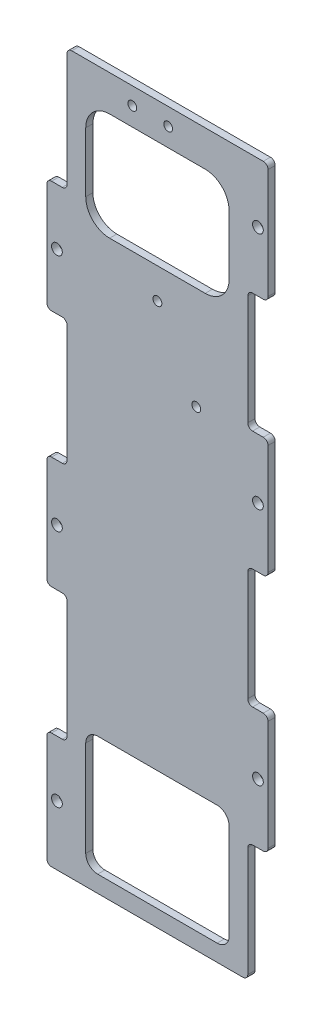
SolidWorks part; units mm, degrees
material "Acrylic (Medium-high impact)"
ref_plane "Front Plane" through (0, 0, 0) normal (0, 0, 1) x (1, 0, 0)
ref_plane "Top Plane" through (0, 0, 0) normal (0, 1, 0) x (1, 0, 0)
ref_plane "Right Plane" through (0, 0, 0) normal (1, 0, 0) x (0, 0, -1)
sketch "Sketch1" plane through (0, 0, 0) normal (0, 0, 1) x (1, 0, 0)
  line L1 (46.3, -150) -> (-46.3, -150)
  line L2 (46.3, -150) -> (46.3, 150)
  line L3 (46.3, 150) -> (-46.3, 150)
  line L4 (-46.3, -150) -> (-46.3, 150)
  line L5 (46.3, -150) -> (-46.3, 150) construction
  line L6 (46.3, 150) -> (-46.3, -150) construction
  point P0 (0, 0)
  dimension "D1" = 92.6
  dimension "D2" = 300
extrude "Boss-Extrude1" add sketch "Sketch1" along normal blind 3
sketch "Sketch2" plane through (0, 0, 0) normal (0, 0, 1) x (1, 0, 0)
  line L0 (-42.06, 150.5) -> (-42.06, -149.5) construction
  line L1 (42.06, 150.5) -> (42.06, -149.5) construction
  line L82 (-37.82, 98.5) -> (-46.3, 98.5)
  line L91 (-37.82, 98.5) -> (-37.82, 150)
  line L104 (-37.82, 150) -> (-46.3, 150)
  line L109 (-46.3, 98.5) -> (-46.3, 150)
  line L112 (-46.3, -150) -> (46.3, -150) construction
  line L115 (-37.82, 98.5) -> (-46.3, 150) construction
  line L116 (-37.82, 150) -> (-46.3, 98.5) construction
  line L121 (37.82, 100) -> (46.3, 100)
  line L122 (37.82, 100) -> (37.82, 50)
  line L127 (37.82, 50) -> (46.3, 50)
  line L128 (46.3, 100) -> (46.3, 50)
  line L133 (37.82, 100) -> (46.3, 50) construction
  line L134 (37.82, 50) -> (46.3, 100) construction
  line L135 (46.3, -50) -> (37.82, -50)
  line L136 (46.3, -50) -> (46.3, 0)
  line L137 (46.3, 0) -> (37.82, 0)
  line L138 (37.82, -50) -> (37.82, 0)
  line L139 (46.3, -50) -> (37.82, 0) construction
  line L140 (46.3, 0) -> (37.82, -50) construction
  line L141 (-37.82, -1.5) -> (-46.3, -1.5)
  line L142 (-37.82, -1.5) -> (-37.82, 51.5)
  line L143 (-37.82, 51.5) -> (-46.3, 51.5)
  line L144 (-46.3, -1.5) -> (-46.3, 51.5)
  line L145 (-37.82, -1.5) -> (-46.3, 51.5) construction
  line L146 (-37.82, 51.5) -> (-46.3, -1.5) construction
  line L147 (-37.82, -101.5) -> (-46.3, -101.5)
  line L148 (-37.82, -101.5) -> (-37.82, -48.5)
  line L149 (-37.82, -48.5) -> (-46.3, -48.5)
  line L150 (-46.3, -101.5) -> (-46.3, -48.5)
  line L151 (-37.82, -101.5) -> (-46.3, -48.5) construction
  line L152 (-37.82, -48.5) -> (-46.3, -101.5) construction
  line L153 (37.82, -150) -> (46.3, -150)
  line L154 (37.82, -150) -> (37.82, -100)
  line L155 (37.82, -100) -> (46.3, -100)
  line L156 (46.3, -150) -> (46.3, -100)
  line L157 (37.82, -150) -> (46.3, -100) construction
  line L158 (37.82, -100) -> (46.3, -150) construction
  line L159 (42.06, 50) -> (-134.3061, 50) construction
  line L160 (46.3, 150) -> (-46.3, 150) construction
  circle A30 centre (-42.06, 75) radius 2.25
  circle A31 centre (42.06, 125) radius 2.25
  circle A32 centre (42.06, 25) radius 2.25
  circle A33 centre (42.06, -75) radius 2.25
  circle A34 centre (-42.06, -25) radius 2.25
  circle A35 centre (-42.06, -125) radius 2.25
  point P8 (-42.06, 124.25)
  point P10 (-42.06, 25)
  point P19 (42.06, 75)
  point P24 (-42.06, -75)
  point P32 (42.06, -25)
  point P39 (42.06, -125)
  dimension "D4" = 84.12
  dimension "D5" = 8.48
  dimension "D15" = 75
  dimension "D17" = 53
  dimension "D23" = 8.48
  dimension "D26" = 0
  dimension "D1" = 4.5
  dimension "D2" = 4.5
  dimension "D12" = 4.5
  dimension "D14" = 4.5
  dimension "D20" = 4.5
  dimension "D22" = 4.5
  dimension "D3" = 25
  dimension "D6" = 51.5
  dimension "D7" = 8.48
  dimension "D8" = 50
  dimension "D9" = 50
  dimension "D10" = 8.48
  dimension "D11" = 75
  dimension "D13" = 100
  dimension "D16" = 53
  dimension "D18" = 8.48
  dimension "D19" = 125
  dimension "D21" = 50
  dimension "D24" = 100
  dimension "D25" = 42.06
  dimension "D27" = 75
  dimension "D28" = 75
  dimension "D29" = 25
  dimension "D30" = 0
  dimension "D31" = 125
extrude "Cut-Extrude1" cut sketch "Sketch2" along normal blind 10
fillet "Fillet1" radius 2 24 edges at (-46.3, 51.5, 1.5) (-37.82, 51.5, 1.5) (-37.82, -1.5, 1.5) (-46.3, -1.5, 1.5) (-46.3, -48.5, 1.5) (-37.82, -48.5, 1.5) (-37.82, -101.5, 1.5) (-46.3, -101.5, 1.5) (-46.3, -150, 1.5) (37.82, -150, 1.5) (37.82, -100, 1.5) (46.3, -100, 1.5) (46.3, -50, 1.5) (37.82, -50, 1.5) (37.82, 0, 1.5) (46.3, 0, 1.5) (46.3, 50, 1.5) (37.82, 50, 1.5) (37.82, 100, 1.5) (46.3, 100, 1.5) (46.3, 150, 1.5) (-37.82, 150, 1.5) (-37.82, 98.5, 1.5) (-46.3, 98.5, 1.5)
sketch "Sketch4" plane through (0, 0, 0) normal (0, 0, -1) x (-1, 0, 0)
  line L0 (0, -150) -> (0, 248.5698) construction
  line L6 (-44.3, 150) -> (35.82, 150) construction
  line L7 (20, 90) -> (-20, 90)
  line L9 (25, -143) -> (-25, -143)
  line L10 (30, -138) -> (30, -98)
  line L11 (25, -93) -> (-25, -93)
  line L12 (-30, -138) -> (-30, -98)
  line L13 (30, -143) -> (-30, -93) construction
  line L14 (30, -93) -> (-30, -143) construction
  line L15 (30, 100) -> (30, 125)
  line L16 (44.3, -150) -> (-35.82, -150) construction
  line L17 (20, 135) -> (-20, 135)
  line L18 (-30, 100) -> (-30, 125)
  line L19 (30, 90) -> (-30, 135) construction
  line L20 (30, 135) -> (-30, 90) construction
  arc A0 (30, -98) -> (25, -93) centre (25, -98) ccw
  arc A1 (25, -143) -> (30, -138) centre (25, -138) ccw
  arc A2 (-25, -143) -> (-30, -138) centre (-25, -138) cw
  arc A3 (-25, -93) -> (-30, -98) centre (-25, -98) ccw
  arc A8 (-20, 135) -> (-30, 125) centre (-20, 125) ccw
  arc A9 (-20, 90) -> (-30, 100) centre (-20, 100) cw
  arc A10 (20, 90) -> (30, 100) centre (20, 100) ccw
  arc A11 (30, 125) -> (20, 135) centre (20, 125) ccw
  point P2 (0, 112.5)
  point P12 (0, -116.8)
  dimension "D7" = 5
  dimension "D8" = 10
  dimension "D1" = 60
  dimension "D2" = 50
  dimension "D3" = 7
  dimension "D4" = 15
  dimension "D5" = 45
  dimension "D6" = 60
extrude "Cut-Extrude3" cut sketch "Sketch4" against normal blind 8.5
sketch "Sketch5" plane through (0, 0, 0) normal (0, 0, -1) x (-1, 0, 0)
  circle A2 centre (0, 77.2) radius 1.85
  circle A3 centre (-16.25, 47) radius 1.85
  dimension "D1" = 3.7
  dimension "D2" = 3.7
extrude "Cut-Extrude4" cut sketch "Sketch5" against normal blind 10
sketch "Sketch6" plane through (0, 0, 0) normal (0, 0, -1) x (-1, 0, 0)
  circle A0 centre (-4.5, 142.75) radius 1.85
  circle A1 centre (10.5, 142.75) radius 1.85
  dimension "D1" = 3.7
  dimension "D2" = 3.7
extrude "Cut-Extrude5" cut sketch "Sketch6" against normal blind 10
